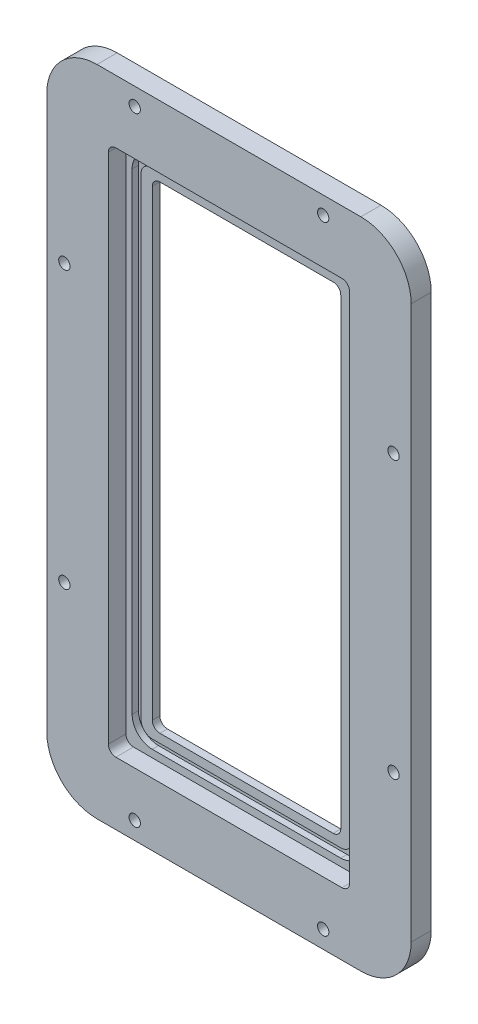
SolidWorks part; units mm, degrees
material "PVC Rígido"
ref_plane "Plano frontal" through (0, 0, 0) normal (0, 0, 1) x (1, 0, 0)
ref_plane "Plano superior" through (0, 0, 0) normal (0, 1, 0) x (1, 0, 0)
ref_plane "Plano direito" through (0, 0, 0) normal (1, 0, 0) x (0, 0, -1)
sketch "Esboço1" plane through (0, 0, 0) normal (0, 0, 1) x (1, 0, 0)
  line L1 (-72.5, -130) -> (72.5, -130)
  line L2 (-72.5, -130) -> (-72.5, 130)
  line L3 (-72.5, 130) -> (72.5, 130)
  line L4 (72.5, -130) -> (72.5, 130)
  line L5 (-72.5, -130) -> (72.5, 130) construction
  line L6 (-72.5, 130) -> (72.5, -130) construction
  point P0 (0, 0)
  dimension "D1" = 145
  dimension "D2" = 260
extrude "Ressalto-extrusão1" add sketch "Esboço1" along normal blind 10
sketch "Esboço2" plane through (0, 0, 0) normal (0, 0, 1) x (1, 0, 0)
  line L1 (-46.5, -110) -> (46.5, -110)
  line L2 (-52.5, -104) -> (-52.5, 104)
  line L3 (-46.5, 110) -> (46.5, 110)
  line L4 (52.5, -104) -> (52.5, 104)
  line L5 (-52.5, -110) -> (52.5, 110) construction
  line L6 (-52.5, 110) -> (52.5, -110) construction
  line L7 (-72.5, -130) -> (72.5, -130)
  line L8 (-72.5, -130) -> (-72.5, 130)
  line L9 (-72.5, 130) -> (72.5, 130)
  line L10 (72.5, -130) -> (72.5, 130)
  line L11 (-72.5, -130) -> (72.5, 130) construction
  line L12 (-72.5, 130) -> (72.5, -130) construction
  arc A0 (-52.5, -104) -> (-46.5, -110) centre (-46.5, -104) ccw
  arc A1 (52.5, -104) -> (46.5, -110) centre (46.5, -104) cw
  arc A2 (52.5, 104) -> (46.5, 110) centre (46.5, 104) ccw
  arc A3 (-46.5, 110) -> (-52.5, 104) centre (-46.5, 104) ccw
  point P0 (0, 0)
  point P6 (0, 0)
  dimension "D3" = 6
  dimension "D1" = 105
  dimension "D2" = 220
extrude "Corte-extrusão3" cut sketch "Esboço2" along normal blind 2
ref_plane "Plano1" through (0, 0, 2) normal (0, 0, -1) x (-1, 0, 0)
sketch "Esboço4" plane through (0, 0, 0) normal (0, 1, 0) x (1, 0, 0)
  line L0 (72.5, -10) -> (72.5, -2) construction
  line L1 (59.265, -2) -> (59.265, -4.765)
  line L2 (72.5, -2) -> (-72.5, -2) construction
  line L3 (59.265, -4.765) -> (55.735, -4.765)
  line L4 (55.735, -2) -> (59.265, -2)
  line L5 (55.735, -4.765) -> (55.735, -2)
  circle A0 centre (57.5, -3) radius 1.765 construction
  dimension "D2" = 3.53
  dimension "D1" = 15
  dimension "D3" = 1
sketch "Esboço5" plane through (0, 0, 0) normal (0, 0, -1) x (-1, 0, 0)
  line L0 (-46.5, 110) -> (46.5, 110) construction
  line L1 (-34.5, -95) -> (34.5, -95)
  line L2 (-37.5, -92) -> (-37.5, 92)
  line L3 (-34.5, 95) -> (34.5, 95)
  line L4 (37.5, -92) -> (37.5, 92)
  line L5 (-37.5, -95) -> (37.5, 95) construction
  line L6 (-37.5, 95) -> (37.5, -95) construction
  line L7 (52.5, 104) -> (52.5, -104) construction
  arc A0 (37.5, -92) -> (34.5, -95) centre (34.5, -92) cw
  arc A1 (-37.5, -92) -> (-34.5, -95) centre (-34.5, -92) ccw
  arc A2 (-37.5, 92) -> (-34.5, 95) centre (-34.5, 92) cw
  arc A3 (34.5, 95) -> (37.5, 92) centre (34.5, 92) cw
  point P0 (0, 0)
  dimension "D3" = 3
  dimension "D1" = 15
  dimension "D2" = 15
extrude "Corte-extrusão4" cut sketch "Esboço5" against normal through all
sketch "Esboço6" plane through (0, 0, 2) normal (0, 0, -1) x (-1, 0, 0)
  line L1 (-65.5, -123) -> (65.5, -123) construction
  line L2 (-65.5, -123) -> (-65.5, 123) construction
  line L3 (-65.5, 123) -> (65.5, 123) construction
  line L4 (65.5, -123) -> (65.5, 123) construction
  line L5 (-65.5, -123) -> (65.5, 123) construction
  line L6 (-65.5, 123) -> (65.5, -123) construction
  line L8 (-46.5, 110) -> (46.5, 110) construction
  line L9 (-52.5, -104) -> (-52.5, 104) construction
  point P0 (0, 0)
  dimension "D1" = 13
  dimension "D2" = 13
hole_wizard "Rebaixo para parafuso com cabeça panela de M41" positions "Esboço8" profile "Esboço7" counterbore size "M4" standard "ISO" end condition through all
sketch "Esboço8" plane through (0, 0, 2) normal (0, 0, -1) x (-1, 0, 0)
  line L0 (-65.5, 123) -> (65.5, 123) construction
  line L1 (65.5, -123) -> (65.5, 123) construction
  line L2 (-65.5, -123) -> (65.5, -123) construction
  line L3 (-65.5, -123) -> (-65.5, 123) construction
  line L11 (72.5, 130) -> (72.5, -130) construction
  line L12 (-72.5, 130) -> (72.5, 130) construction
  line L13 (72.5, -130) -> (-72.5, -130) construction
  line L14 (-72.5, -130) -> (-72.5, 130) construction
  point P0 (-37.5, 123)
  point P1 (37.5, 123)
  point P5 (65.5, 55)
  point P9 (65.5, -55)
  point P11 (37.5, -123)
  point P15 (-37.5, -123)
  point P17 (-65.5, -55)
  point P21 (-65.5, 55)
  dimension "D1" = 35
  dimension "D2" = 35
  dimension "D3" = 35
  dimension "D4" = 35
  dimension "D5" = 75
  dimension "D6" = 75
  dimension "D7" = 75
  dimension "D8" = 75
sketch "Esboço7" plane through (37.5, 123, 2) normal (1, 0, 0) x (0, 1, 0)
  line L0 (0, 0) -> (0, 8)
  line L1 (0, 8) -> (2.25, 8)
  line L3 (2.25, 8) -> (2.25, 3.1)
  line L4 (2.25, 3.1) -> (4.5, 3.1)
  line L5 (4.5, 3.1) -> (4.5, 0)
  line L7 (4.5, 0) -> (0, 0)
  line L11 (0, -6.35) -> (0, 107.95) construction
  dimension "Thru Hole Dia." = 4.5
  dimension "Thru Hole Depth" = 8
  dimension "C'Bore Dia." = 9
  dimension "C'Bore Depth" = 3.1
sketch "Esboço9" plane through (0, 0, 10) normal (0, 0, 1) x (1, 0, 0)
  line L1 (-45, -105) -> (45, -105)
  line L2 (-48, -102) -> (-48, 102)
  line L3 (-45, 105) -> (45, 105)
  line L4 (48, -102) -> (48, 102)
  line L5 (-48, -105) -> (48, 105) construction
  line L6 (-48, 105) -> (48, -105) construction
  arc A0 (-45, 105) -> (-48, 102) centre (-45, 102) ccw
  arc A1 (-48, -102) -> (-45, -105) centre (-45, -102) ccw
  arc A2 (48, -102) -> (45, -105) centre (45, -102) cw
  arc A3 (48, 102) -> (45, 105) centre (45, 102) ccw
  point P0 (0, 0)
  dimension "D3" = 3
  dimension "D1" = 96
  dimension "D2" = 210
extrude "Corte-extrusão5" cut sketch "Esboço9" against normal blind 7
ref_plane "Plano2" through (0, 0, 3) normal (0, 0, 1) x (1, 0, 0)
sketch "Esboço11" plane through (0, 0, 3) normal (0, 0, 1) x (1, 0, 0)
  line L1 (-37.5, -100) -> (37.5, -100)
  line L2 (-43.5, -94) -> (-43.5, 94)
  line L3 (-37.5, 100) -> (37.5, 100)
  line L4 (43.5, -94) -> (43.5, 94)
  line L5 (-43.5, -100) -> (43.5, 100) construction
  line L6 (-43.5, 100) -> (43.5, -100) construction
  arc A0 (-43.5, -94) -> (-37.5, -100) centre (-37.5, -94) ccw
  arc A1 (37.5, -100) -> (43.5, -94) centre (37.5, -94) ccw
  arc A2 (43.5, 94) -> (37.5, 100) centre (37.5, 94) ccw
  arc A3 (-37.5, 100) -> (-43.5, 94) centre (-37.5, 94) ccw
  point P0 (0, 0)
  dimension "D3" = 6
  dimension "D1" = 87
  dimension "D2" = 200
sketch "Esboço14" plane through (0, 0, 2) normal (0, 0, -1) x (-1, 0, 0)
  line L0 (-72.5, 130) -> (72.5, 130) construction
  line L1 (-47.5, -115) -> (47.5, -115)
  line L2 (-57.5, -105) -> (-57.5, 105)
  line L3 (-47.5, 115) -> (47.5, 115)
  line L4 (57.5, -105) -> (57.5, 105)
  line L5 (-57.5, -115) -> (57.5, 115) construction
  line L6 (-57.5, 115) -> (57.5, -115) construction
  line L7 (-72.5, -130) -> (-72.5, 130) construction
  arc A0 (57.5, -105) -> (47.5, -115) centre (47.5, -105) cw
  arc A1 (-47.5, -115) -> (-57.5, -105) centre (-47.5, -105) cw
  arc A2 (-57.5, 105) -> (-47.5, 115) centre (-47.5, 105) cw
  arc A3 (47.5, 115) -> (57.5, 105) centre (47.5, 105) cw
  point P0 (0, 0)
  dimension "D3" = 10
  dimension "D1" = 15
  dimension "D2" = 15
sweep "Varredura de corte3" cut profiles "Esboço4" path "Esboço14"
sketch "Esboço13" plane through (0, 0, 0) normal (0, 1, 0) x (1, 0, 0)
  line L0 (45, -3) -> (-45, -3) construction
  line L1 (42, -5.5) -> (45.53, -5.5) construction
  line L2 (42, -5.5) -> (42, -0.5) construction
  line L3 (42, -0.5) -> (45.53, -0.5)
  line L4 (45.53, -5.5) -> (45.53, -0.5) construction
  line L5 (42, -5.5) -> (45.53, -0.5) construction
  line L6 (42, -0.5) -> (45.53, -5.5) construction
  line L7 (37.5, -3) -> (43.5, -3) construction
  line L8 (42, -0.5) -> (42, -3)
  line L9 (45.53, -0.5) -> (45.53, -3)
  line L10 (45.53, -3) -> (42, -3)
  point P0 (43.765, -3)
  dimension "D1" = 3.53
  dimension "D2" = 2.5
sweep "Varredura de corte2" cut profiles "Esboço13" path "Esboço11"
fillet "Filete1" radius 20 4 edges at (-72.5, -130, 6) (72.5, -130, 6) (72.5, 130, 6) (-72.5, 130, 6)
